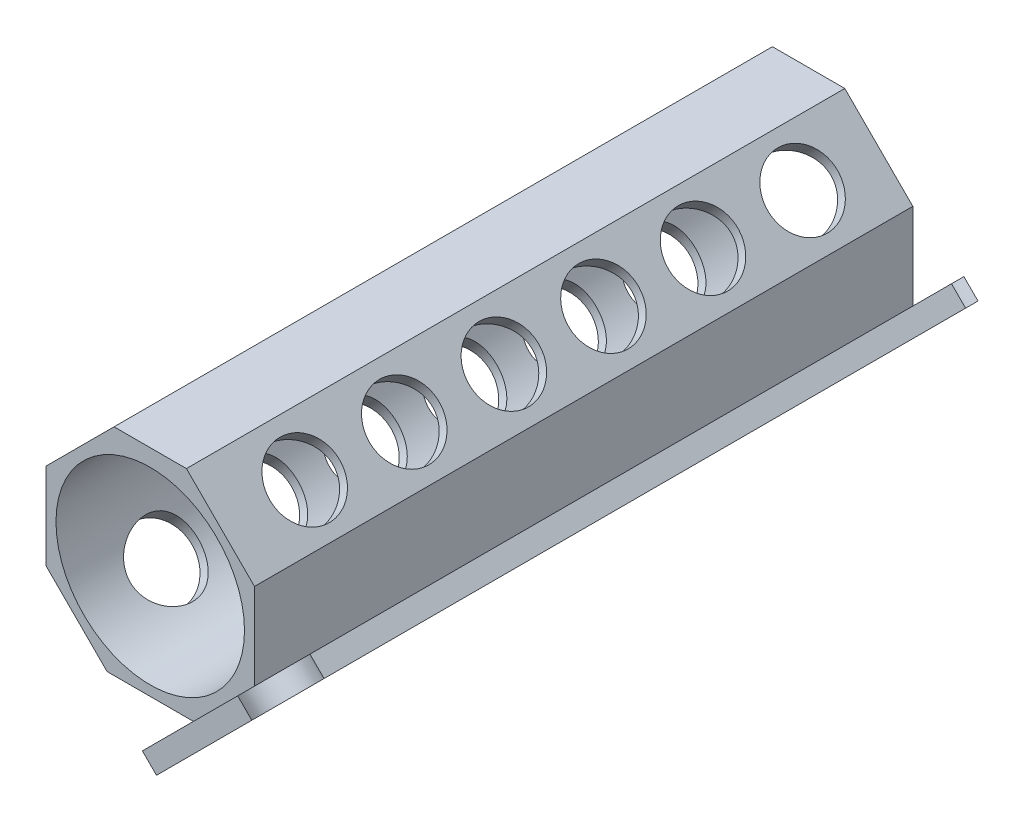
SolidWorks part; units mm, degrees
ref_plane "Ebene vorne" through (0, 0, 0) normal (1, 0, 0) x (0, 1, 0)
ref_plane "Ebene oben" through (0, 0, 0) normal (0, 0, 1) x (0, 1, 0)
ref_plane "Ebene rechts" through (0, 0, 0) normal (0, 1, 0) x (-1, 0, 0)
sketch "Skizze1" plane through (0, 0, 0) normal (0, 0, 1) x (0, 1, 0)
  line L0 (11.1508, 3.6277) -> (11.1508, -3.6277)
  line L13 (11.1508, 3.6277) -> (4.3285, 10.45)
  line L14 (4.3285, 10.45) -> (-4.3285, 10.45)
  line L15 (-4.3285, 10.45) -> (-10.45, 4.3285)
  line L16 (-10.45, 4.3285) -> (-10.45, -4.3285)
  line L17 (-10.45, -4.3285) -> (-4.3285, -10.45)
  line L18 (-4.3285, -10.45) -> (4.3285, -10.45)
  line L19 (4.3285, -10.45) -> (11.1508, -3.6277)
  line L29 (10.45, -2.605) -> (10.45, 5.6378) [skipped]
  circle A0 centre (0, 0) radius 9.45
  circle A1 centre (0, 0) radius 10.45 construction
  dimension "D1" = 18.9
  dimension "D2" = 20.9
extrude "Aufsatz-Linear austragen1" add sketch "Skizze1" along normal blind 66
sketch "Skizze9" plane through (7.3893, 7.3893, 0) normal (0.7071, 0.7071, 0) x (-0.7071, 0.7071, 0)
  line L0 (0.4955, 66) -> (0, 0) construction
  line L1 (-4.3285, 66) -> (5.3196, 66) construction
  circle A0 centre (0.4325, 57.6) radius 3.5
  circle A1 centre (0.4566, 47.6) radius 3.5
  circle A2 centre (0.4807, 37.6001) radius 3.5
  circle A3 centre (0.5048, 27.6001) radius 3.5
  circle A4 centre (0.5289, 17.6001) radius 3.5
  circle A5 centre (0.553, 7.6001) radius 3.5
  dimension "D1" = 7
  dimension "D2" = 8.4
  dimension "D3" = 6
extrude "Schnitt-Linear austragen8" cut sketch "Skizze9" against normal through all
sketch "Skizze13" plane through (7.3893, -7.3893, 0) normal (0.7071, -0.7071, 0) x (0.7071, 0.7071, 0)
  line L0 (0, 66) -> (0, 0) construction
  line L1 (-11, -3.4) -> (11, -3.4)
  line L2 (-11, -3.4) -> (-11, 69.4)
  line L3 (-11, 69.4) -> (11, 69.4)
  line L4 (11, -3.4) -> (11, 69.4)
  line L5 (-11, -3.4) -> (11, 69.4) construction
  line L6 (-11, 69.4) -> (11, -3.4) construction
  line L7 (-4.3285, 66) -> (4.3285, 66) construction
  point P0 (0, 33)
  point P10 (0, 0)
  point P11 (0, 33)
  dimension "D1" = 22
  dimension "D2" = 72.8
extrude "Aufsatz-Linear austragen2" add sketch "Skizze13" along normal blind 2
sketch "Skizze14" plane through (8.8035, -8.8035, 0) normal (0.7071, -0.7071, 0) x (0.7071, 0.7071, 0)
  circle A0 centre (8.88, 67.28) radius 3
  circle A2 centre (-8.88, -1.28) radius 3
  circle A3 centre (8.88, -1.28) radius 3
  circle A4 centre (-8.88, 67.28) radius 3
  point P2 (0, 0)
  point P3 (0, 0)
  dimension "D1" = 6
  dimension "D2" = 2.12
  dimension "D3" = 6
  dimension "D4" = 6
  dimension "D8" = 6
  dimension "D5" = 2.12
  dimension "D6" = 2.12
  dimension "D7" = 2.12
  dimension "D9" = 2.12
  dimension "D10" = 2.12
  dimension "D11" = 2.12
  dimension "D12" = 2.12
extrude "Schnitt-Linear austragen12" cut sketch "Skizze14" against normal blind 2
